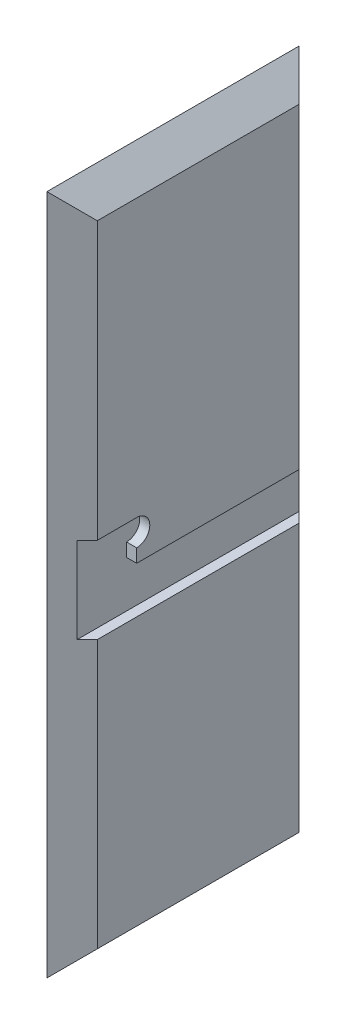
SolidWorks part; units mm, degrees
ref_plane "Front Plane" through (0, 0, 0) normal (0, 0, 1) x (1, 0, 0)
ref_plane "Top Plane" through (0, 0, 0) normal (0, 1, 0) x (1, 0, 0)
ref_plane "Right Plane" through (0, 0, 0) normal (1, 0, 0) x (0, 0, -1)
sketch "Sketch1" plane through (0, 0, 0) normal (1, 0, 0) x (0, 0, -1)
  line L1 (-63.5, 171.45) -> (63.5, 171.45)
  line L2 (-63.5, 171.45) -> (-63.5, -171.45)
  line L3 (-63.5, -171.45) -> (63.5, -171.45)
  line L4 (63.5, 171.45) -> (63.5, -171.45)
  line L8 (-63.5, 171.45) -> (63.5, -171.45) construction
  line L9 (-63.5, 171.45) -> (63.5, 171.45) construction
  line L10 (-63.5, 171.45) -> (-63.5, -171.45) construction
extrude "Boss-Extrude1" add sketch "Sketch1" along normal blind 12.7
draft "Draft1" type of draft neutral plane draft angle 45 faces to draft 4 face at (6.35, -171.45, 0) face at (6.35, 0, -63.5) face at (6.35, 0, 63.5) face at (6.35, 171.45, 0) neutral plane through (0, 0, 0) neutral plane normal (-1, 0, 0) reverse direction yes parameters "D1"=45
sketch "Sketch2" plane through (12.7, 0, 0) normal (1, 0, 0) x (0, 0, -1)
  line L0 (-63.5, 171.45) -> (-63.5, -171.45) construction
  line L1 (-63.5, 19.431) -> (-30.988, 19.431)
  line L2 (-63.5, 19.431) -> (-63.5, -23.876)
  line L4 (-30.988, 6.223) -> (-30.988, -0.508)
  line L5 (0, 0) -> (63.5, 0) construction
  line L6 (63.5, -171.45) -> (63.5, 171.45) construction
  line L7 (-63.5, -23.876) -> (63.5, -23.876)
  line L8 (63.5, -23.876) -> (63.5, -0.508)
  line L9 (63.5, -0.508) -> (-30.988, -0.508)
  line L10 (-50.419, 19.05) -> (-31.369, 19.05) construction
  line L11 (-31.369, -19.05) -> (-31.369, 19.05) construction
  arc A0 (-30.988, 19.431) -> (-30.988, 6.223) centre (-30.988, 12.827) cw
  dimension "D1" = 6.604
  dimension "D2" = 0.381
  dimension "D3" = 0.381
  dimension "D4" = 0.508
  dimension "D5" = 23.368
extrude "Cut-Extrude1" cut sketch "Sketch2" against normal blind 5.08 and the other way through all
